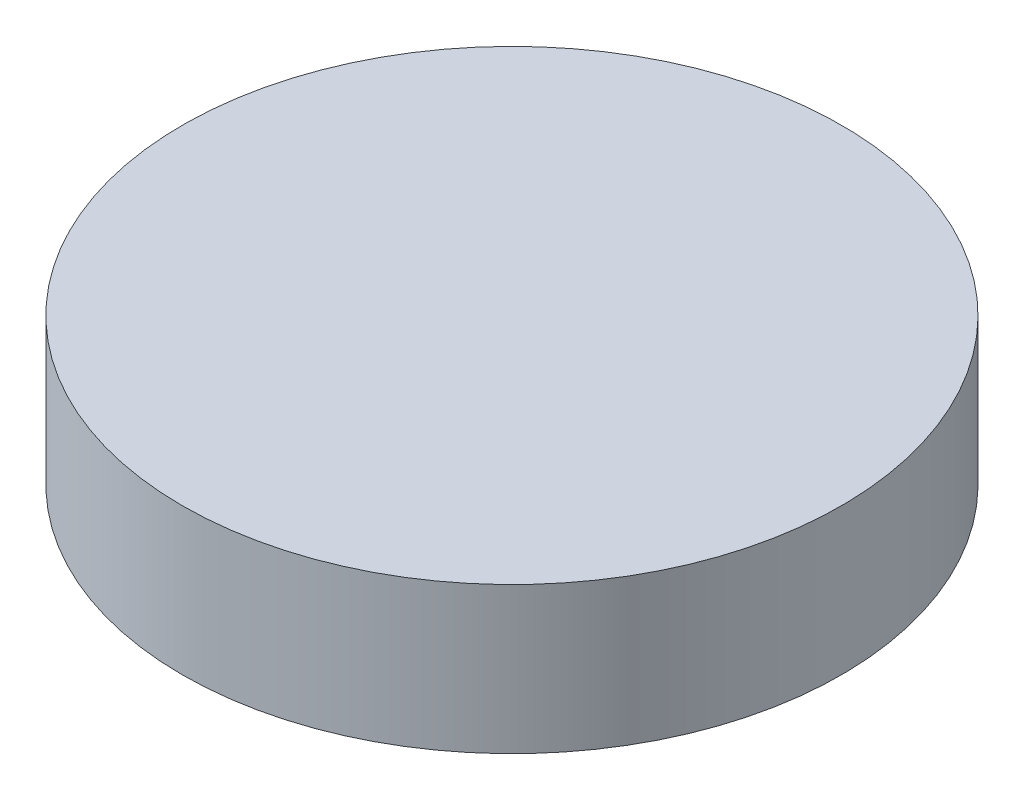
SolidWorks part; units mm, degrees
ref_plane "Front Plane" through (0, 0, 0) normal (0, 0, 1) x (1, 0, 0)
ref_plane "Top Plane" through (0, 0, 0) normal (0, 1, 0) x (1, 0, 0)
ref_plane "Right Plane" through (0, 0, 0) normal (1, 0, 0) x (0, 0, -1)
sketch "Sketch1" plane through (0, 0, 0) normal (0, 1, 0) x (1, 0, 0)
  circle A0 centre (0, 0) radius 90
  dimension "D1" = 180
sketch "Sketch2" plane through (0, 0, 0) normal (0, 1, 0) x (1, 0, 0)
  circle A0 centre (0, 0) radius 90
extrude "Boss-Extrude1" add sketch "Sketch2" along normal blind 40
sketch "Sketch3" plane through (0, 0, 0) normal (0, -1, 0) x (-1, 0, 0)
  circle A0 centre (0, 0) radius 25
  dimension "D1" = 50
sketch "Sketch4" plane through (0, 0, 0) normal (0, -1, 0) x (-1, 0, 0)
  circle A0 centre (0, 0) radius 25
extrude "Boss-Extrude2" add sketch "Sketch4" along normal blind 5
sketch "Sketch5" plane through (0, -5, 0) normal (0, -1, 0) x (-1, 0, 0)
  circle A0 centre (0, 0) radius 20
  dimension "D1" = 40
sketch "Sketch6" plane through (0, -5, 0) normal (0, -1, 0) x (-1, 0, 0)
  circle A0 centre (0, 0) radius 20
extrude "Boss-Extrude3" add sketch "Sketch6" along normal blind 40
